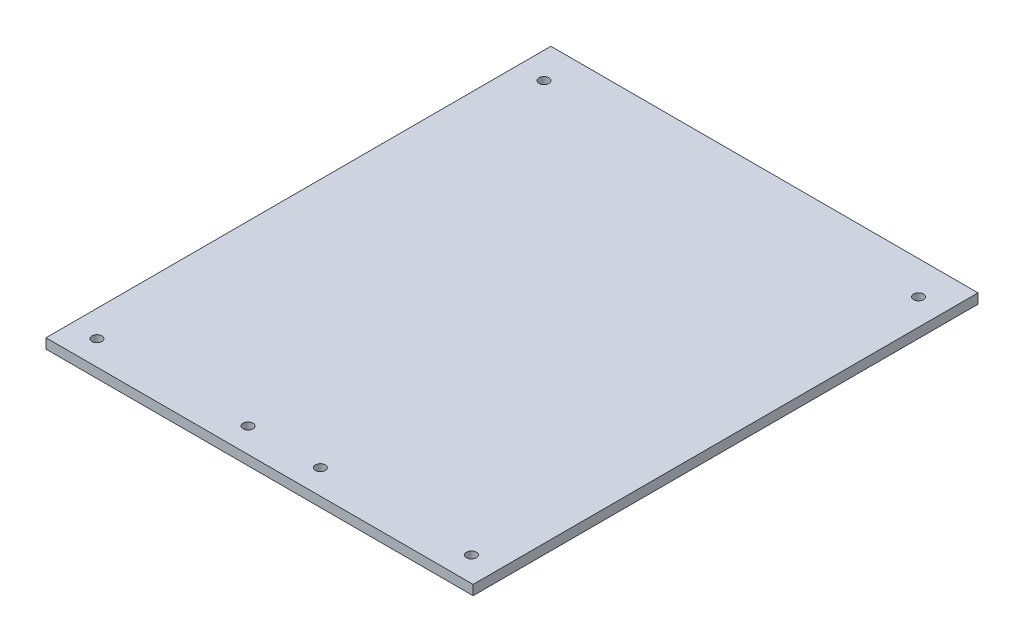
SolidWorks part; units mm, degrees
ref_plane "Front Plane" through (0, 0, 0) normal (0, 0, 1) x (1, 0, 0)
ref_plane "Top Plane" through (0, 0, 0) normal (0, 1, 0) x (1, 0, 0)
ref_plane "Right Plane" through (0, 0, 0) normal (1, 0, 0) x (0, 0, -1)
sketch "Sketch2" plane through (0, 0, 0) normal (0, 1, 0) x (1, 0, 0)
  line L0 (65, 153.666) -> (65, 0) construction
  line L1 (0, 0) -> (130, 0)
  line L2 (0, 0) -> (0, 153.666)
  line L3 (0, 153.666) -> (130, 153.666)
  line L4 (130, 0) -> (130, 153.666)
  circle A0 centre (8, 143.566) radius 1.5
  circle A1 centre (8, 7.5) radius 1.5
  circle A2 centre (54, 7.5) radius 1.5
  circle A3 centre (122, 7.5) radius 1.5
  circle A4 centre (76, 7.5) radius 1.5
  circle A5 centre (122, 143.566) radius 1.5
  point P13 (0, 0)
  point P15 (52.4128, 5.3591)
  dimension "D3" = 3
  dimension "D1" = 153.666
  dimension "D2" = 130
  dimension "D4" = 10.1
  dimension "D5" = 8
  dimension "D6" = 46
  dimension "D7" = 8
  dimension "D8" = 7.5
extrude "Boss-Extrude1" add sketch "Sketch2" along normal blind 3
